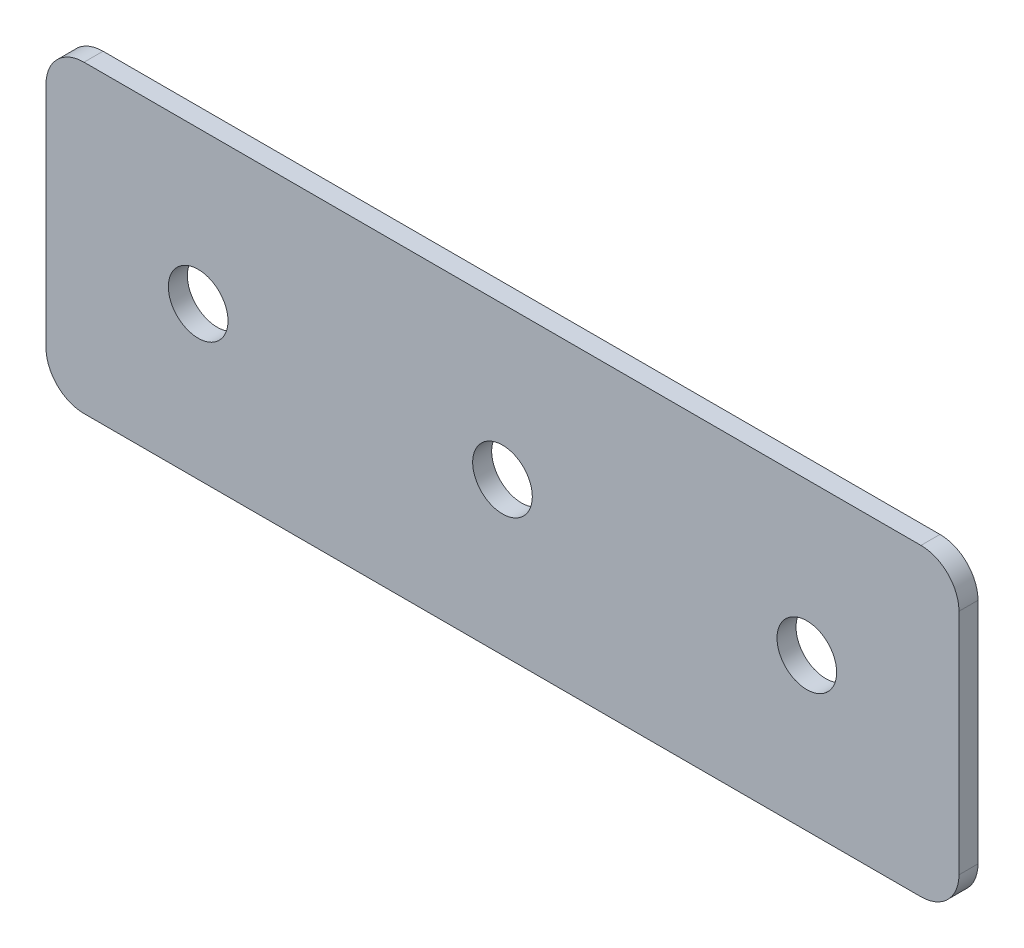
SolidWorks part; units mm, degrees
material "6061-T6 (SS)"
ref_plane "Front Plane" through (0, 0, 0) normal (0, 0, 1) x (1, 0, 0)
ref_plane "Top Plane" through (0, 0, 0) normal (0, 1, 0) x (1, 0, 0)
ref_plane "Right Plane" through (0, 0, 0) normal (1, 0, 0) x (0, 0, -1)
sketch "Sketch1" plane through (0, 0, 0) normal (0, 0, 1) x (1, 0, 0)
  line L1 (0, 0) -> (76.2, 0)
  line L2 (0, 0) -> (0, 25.4)
  line L3 (0, 25.4) -> (76.2, 25.4)
  line L4 (76.2, 0) -> (76.2, 25.4)
  dimension "D1" = 25.4
  dimension "D2" = 76.2
extrude "Boss-Extrude1" add sketch "Sketch1" against normal blind 1.5875
sketch "Sketch2" plane through (0, 0, 0) normal (0, 0, 1) x (1, 0, 0)
  line L0 (0, 0) -> (76.2, 0) construction
  line L1 (0, 25.4) -> (0, 0) construction
  line L2 (12.7, 12.7) -> (38.1, 12.7) construction
  circle A0 centre (12.7, 12.7) radius 2.4892
  circle A1 centre (38.1, 12.7) radius 2.4892
  circle A2 centre (63.5, 12.7) radius 2.4892
  circle A3 centre (88.9, 12.7) radius 2.4892
  circle A4 centre (114.3, 12.7) radius 2.4892
  dimension "D1" = 4.9784
  dimension "D2" = 12.7
  dimension "D3" = 12.7
  dimension "D5" = 25.4
  dimension "D4" = 5
extrude "Cut-Extrude1" cut sketch "Sketch2" against normal through all
fillet "Fillet1" radius 3.175 4 edges at (0, 0, -0.7937) (76.2, 0, -0.7937) (76.2, 25.4, -0.7937) (0, 25.4, -0.7937)
